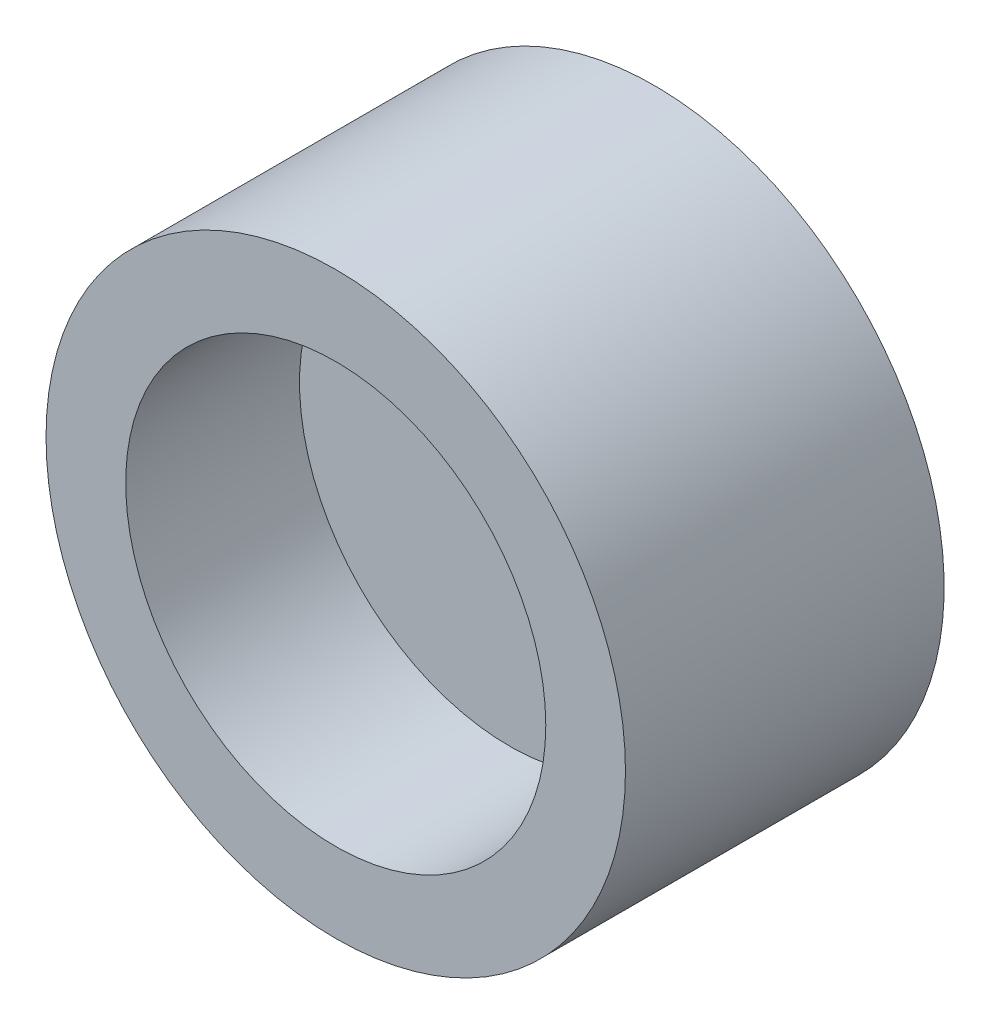
SolidWorks part; units mm, degrees
ref_plane "Front Plane" through (0, 0, 0) normal (0, 0, 1) x (1, 0, 0)
ref_plane "Top Plane" through (0, 0, 0) normal (0, 1, 0) x (1, 0, 0)
ref_plane "Right Plane" through (0, 0, 0) normal (1, 0, 0) x (0, 0, -1)
sketch "Sketch1" plane through (0, 0, 0) normal (0, 0, 1) x (1, 0, 0)
  circle A0 centre (0, 0) radius 2
  circle A1 centre (0, 0) radius 1.45
  dimension "D1" = 2.9
  dimension "D2" = 4
extrude "Boss-Extrude1" add sketch "Sketch1" along normal blind 1.2
sketch "Sketch2" plane through (0, 0, 0) normal (0, 0, -1) x (-1, 0, 0)
  circle A0 centre (0, 0) radius 2
  circle A2 centre (0, 0) radius 2 construction
extrude "Boss-Extrude2" add sketch "Sketch2" along normal blind 1
